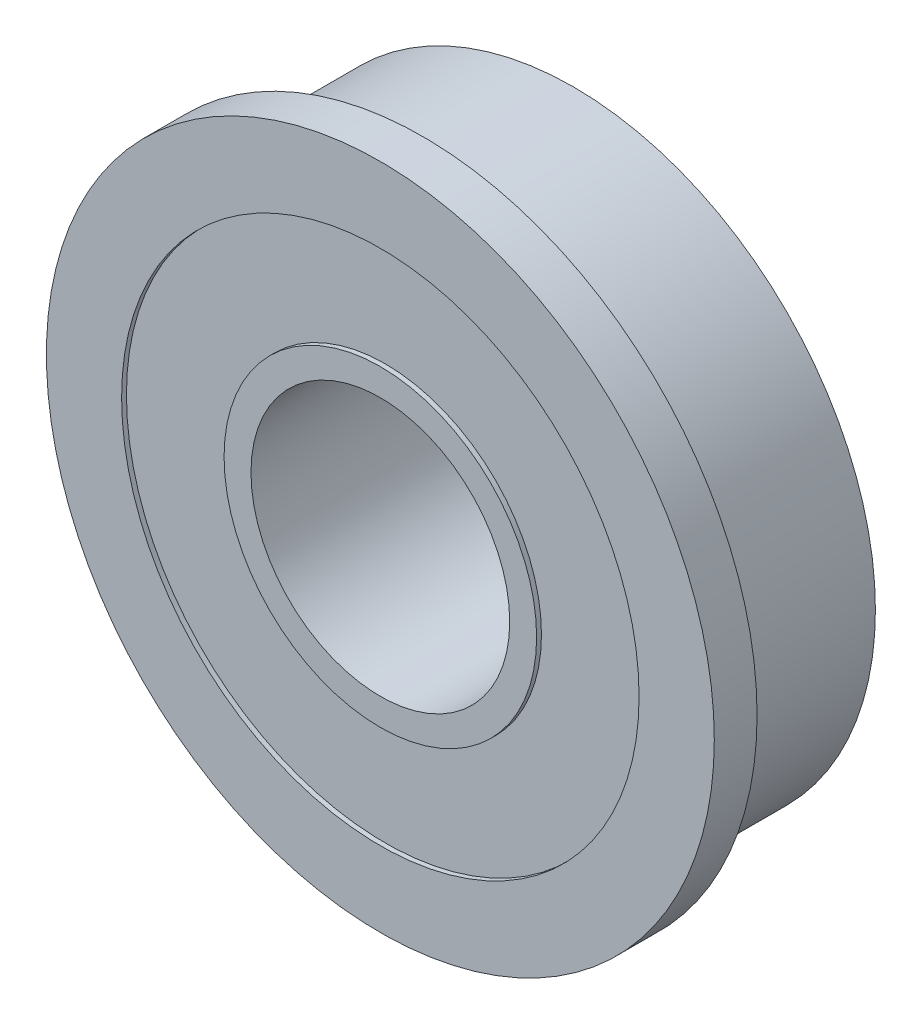
SolidWorks part; units mm, degrees
material "AISI 4130 Steel, annealed at 865C"
ref_plane "Front Plane" through (0, 0, 0) normal (0, 0, 1) x (1, 0, 0)
ref_plane "Top Plane" through (0, 0, 0) normal (0, 1, 0) x (1, 0, 0)
ref_plane "Right Plane" through (0, 0, 0) normal (1, 0, 0) x (0, 0, -1)
sketch "Sketch1" plane through (0, 0, 0) normal (0, 1, 0) x (1, 0, 0)
  line L0 (4.7625, -3.556) -> (5.7531, -3.556)
  line L1 (5.7531, -3.556) -> (5.7531, -3.3782)
  line L2 (5.7531, -3.3782) -> (9.525, -3.3782)
  line L3 (9.525, -3.3782) -> (9.525, -3.556)
  line L4 (9.525, -3.556) -> (12.2936, -3.556)
  line L5 (12.2936, -3.556) -> (12.2936, -1.9812)
  line L6 (12.2936, -1.9812) -> (11.1125, -1.9812)
  line L7 (11.1125, -1.9812) -> (11.1125, 3.556)
  line L8 (11.1125, 3.556) -> (9.525, 3.556)
  line L9 (9.525, 3.556) -> (9.525, 3.3782)
  line L10 (9.525, 3.3782) -> (5.7531, 3.3782)
  line L11 (5.7531, 3.3782) -> (5.7531, 3.556)
  line L12 (5.7531, 3.556) -> (4.7625, 3.556)
  line L13 (4.7625, 3.556) -> (4.7625, -3.556)
  line L14 (0, 3.556) -> (0, -3.556) construction
  dimension "D1" = 4.7625
  dimension "D2" = 0.9906
  dimension "D3" = 3.7719
  dimension "D4" = 1.5875
  dimension "D5" = 5.5372
  dimension "D6" = 1.5748
  dimension "D7" = 2.7686
revolve "Revolve1" add sketch "Sketch1" angle 360 about L14
